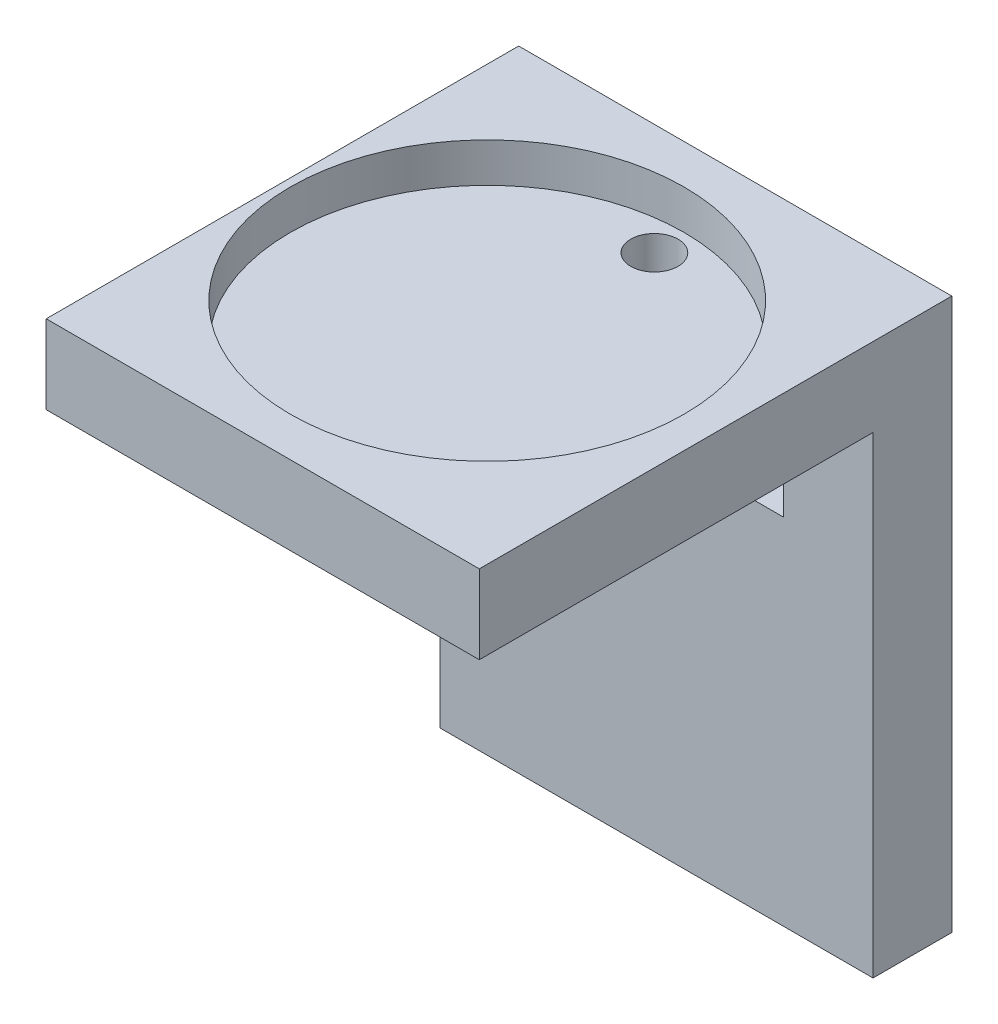
SolidWorks part; units mm, degrees
ref_plane "정면" through (0, 0, 0) normal (0, 0, 1) x (1, 0, 0)
ref_plane "윗면" through (0, 0, 0) normal (0, 1, 0) x (1, 0, 0)
ref_plane "우측면" through (0, 0, 0) normal (1, 0, 0) x (0, 0, -1)
sketch "Sketch1" plane through (0, 0, 0) normal (0, 1, 0) x (1, 0, 0)
  line L1 (0, 0) -> (670, 0)
  line L2 (0, 0) -> (0, 120)
  line L3 (0, 120) -> (670, 120)
  line L4 (670, 0) -> (670, 120)
  dimension "700" = 670
  dimension "D2" = 120
extrude "Boss-Extrude1" add sketch "Sketch1" along normal blind 530
sketch "Sketch2" plane through (0, 0, 0) normal (0, 0, 1) x (1, 0, 0)
  line L0 (0, 530) -> (0, 0) construction
  line L1 (10, 280) -> (110, 280)
  line L2 (10, 280) -> (10, 480)
  line L3 (10, 480) -> (110, 480)
  line L4 (110, 280) -> (110, 480)
  line L5 (0, 0) -> (670, 0) construction
  line L6 (120, 280) -> (120, 480)
  line L7 (120, 280) -> (220, 280)
  line L8 (220, 280) -> (220, 480)
  line L9 (120, 480) -> (220, 480)
  line L10 (230, 280) -> (230, 480)
  line L11 (230, 280) -> (330, 280)
  line L12 (330, 280) -> (330, 480)
  line L13 (230, 480) -> (330, 480)
  line L14 (340, 280) -> (340, 480)
  line L15 (340, 280) -> (440, 280)
  line L16 (440, 280) -> (440, 480)
  line L17 (340, 480) -> (440, 480)
  line L18 (450, 280) -> (450, 480)
  line L19 (450, 280) -> (550, 280)
  line L20 (550, 280) -> (550, 480)
  line L21 (450, 480) -> (550, 480)
  line L22 (560, 280) -> (560, 480)
  line L23 (560, 280) -> (660, 280)
  line L24 (660, 280) -> (660, 480)
  line L25 (560, 480) -> (660, 480)
  line L27 (10, 10) -> (660, 10)
  line L28 (10, 10) -> (10, 260)
  line L29 (10, 260) -> (660, 260)
  line L30 (660, 10) -> (660, 260)
  line L31 (0, 530) -> (670, 530) construction
  point P6 (10, 380)
  dimension "D1" = 100
  dimension "D2" = 200
  dimension "D3" = 10
  dimension "D4" = 50
  dimension "D6" = 10
  dimension "D7" = 20
  dimension "D5" = 6
extrude "Cut-Extrude1" cut sketch "Sketch2" against normal blind 100
sketch "Sketch3" plane through (0, 530, 0) normal (0, 1, 0) x (1, 0, 0)
  line L1 (670, 120) -> (0, 120) construction
  line L2 (0, 120) -> (0, 0) construction
  circle A0 centre (60, 60) radius 50
  circle A1 centre (170, 60) radius 50
  circle A2 centre (280, 60) radius 50
  circle A3 centre (390, 60) radius 50
  circle A4 centre (500, 60) radius 50
  circle A5 centre (610, 60) radius 50
  dimension "D1" = 100
  dimension "D2" = 10
  dimension "D3" = 10
  dimension "D4" = 6
extrude "Cut-Extrude2" cut sketch "Sketch3" against normal blind 260
hole_wizard "Ø12.0 (12) Diameter Hole2" positions "3DSketch1" profile "Sketch7" hole size "Ø12.0" standard "Ansi Metric"
sketch3d "3DSketch1"
  point P0 (59.7046, 270, -102.4117)
  point P2 (171.5567, 270, -102.6076)
  point P4 (280.8723, 270, -102.3969)
  point P6 (391.0687, 270, -102.7535)
  point P8 (500.7133, 270, -101.754)
  point P10 (609.5165, 270, -101.1227)
sketch "Sketch7" plane through (59.7046, 270, -102.4117) normal (1, 0, 0) x (0, 0, 1)
  line L0 (0, 0) -> (0, 33.6052)
  line L1 (0, 33.6052) -> (6, 30)
  line L2 (6, 30) -> (6, 0)
  line L5 (6, 0) -> (0, 0)
  line L10 (0, 33.6052) -> (-6, 30) construction
  line L11 (0, -6.35) -> (0, 107.95) construction
  dimension "구멍 지름" = 12
  dimension "구멍 깊이" = 30
  dimension "드릴 각도" = 118
sketch "Sketch8" plane through (0, 0, 0) normal (0, 0, 1) x (1, 0, 0)
  line L0 (660, 280) -> (660, 480) construction
  line L1 (10, 280) -> (660, 280)
  line L2 (10, 280) -> (10, 330)
  line L3 (10, 330) -> (660, 330)
  line L4 (660, 280) -> (660, 330)
  dimension "D1" = 50
extrude "Boss-Extrude2" add sketch "Sketch8" against normal blind 5
sketch "Sketch9" plane through (670, 0, 0) normal (1, 0, 0) x (0, 0, -1)
  line L0 (0, 530) -> (0, 0) construction
  line L1 (10, 10) -> (20, 10)
  line L2 (10, 10) -> (10, 260)
  line L3 (10, 260) -> (20, 260)
  line L4 (20, 10) -> (20, 260)
  line L5 (0, 0) -> (120, 0) construction
  dimension "D1" = 10
  dimension "D2" = 10
  dimension "D3" = 10
  dimension "D4" = 250
extrude "Cut-Extrude3" cut sketch "Sketch9" against normal blind 717
sketch "Sketch10" plane through (0, 10, 0) normal (0, 1, 0) x (1, 0, 0)
  line L0 (670, 120) -> (0, 120) construction
  line L1 (365, 61.9436) -> (350, 87.9243)
  line L2 (350, 87.9243) -> (320, 87.9243)
  line L3 (320, 87.9243) -> (305, 61.9436)
  line L4 (305, 61.9436) -> (320, 35.9628)
  line L5 (320, 35.9628) -> (350, 35.9628)
  line L6 (350, 35.9628) -> (365, 61.9436)
  line L7 (0, 120) -> (0, 0) construction
  circle A0 centre (335, 61.9436) radius 25.9808 construction
  dimension "D1" = 60
  dimension "D2" = 305
extrude "Cut-Extrude4" cut sketch "Sketch10" against normal blind 5
sketch "Sketch11" plane through (0, 0, -100) normal (0, 0, 1) x (1, 0, 0)
  line L0 (10, 10) -> (660, 10) construction
  line L1 (250, 10) -> (260, 10)
  line L2 (250, 10) -> (250, 110)
  line L3 (250, 110) -> (260, 110)
  line L4 (260, 10) -> (260, 110)
  line L5 (660, 10) -> (660, 260) construction
  line L6 (410, 10) -> (420, 10)
  line L7 (410, 10) -> (410, 110)
  line L8 (410, 110) -> (420, 110)
  line L9 (420, 10) -> (420, 110)
  line L10 (25, 198.4569) -> (325, 145.5588)
  line L11 (325, 145.5588) -> (325, 122.0178)
  line L12 (325, 122.0178) -> (345, 122.0178)
  line L13 (345, 122.0178) -> (345, 145.5588)
  line L14 (345, 145.5588) -> (645, 198.4569)
  line L15 (645, 198.4569) -> (25, 198.4569)
  point P18 (345, 133.7883)
  dimension "D1" = 10
  dimension "D2" = 10
  dimension "D3" = 100
  dimension "D4" = 100
  dimension "D5" = 150
  dimension "D6" = 240
  dimension "D7" = 20
  dimension "D8" = 65
  dimension "D9" = 100
  dimension "D10" = 620
  dimension "D11" = 100
extrude "Boss-Extrude3" add sketch "Sketch11" along normal blind 78 separate body
sketch "Sketch12" plane through (0, 0, -100) normal (0, 0, 1) x (1, 0, 0)
  line L0 (660, 260) -> (10, 260) construction
  line L1 (75.1986, 260) -> (95.1986, 260)
  line L2 (75.1986, 260) -> (75.1986, 230)
  line L3 (75.1986, 230) -> (95.1986, 230)
  line L4 (95.1986, 260) -> (95.1986, 230)
  line L5 (65.1986, 260) -> (65.1986, 240) construction
  line L6 (185.1986, 260) -> (185.1986, 230)
  line L7 (185.1986, 260) -> (205.1986, 260)
  line L8 (205.1986, 260) -> (205.1986, 230)
  line L9 (185.1986, 230) -> (205.1986, 230)
  line L10 (295.1986, 260) -> (295.1986, 230)
  line L11 (295.1986, 260) -> (315.1986, 260)
  line L12 (315.1986, 260) -> (315.1986, 230)
  line L13 (295.1986, 230) -> (315.1986, 230)
  line L14 (405.1986, 260) -> (405.1986, 230)
  line L15 (405.1986, 260) -> (425.1986, 260)
  line L16 (425.1986, 260) -> (425.1986, 230)
  line L17 (405.1986, 230) -> (425.1986, 230)
  line L18 (515.1986, 260) -> (515.1986, 230)
  line L19 (515.1986, 260) -> (535.1986, 260)
  line L20 (535.1986, 260) -> (535.1986, 230)
  line L21 (515.1986, 230) -> (535.1986, 230)
  line L22 (625.1986, 260) -> (625.1986, 230)
  line L23 (625.1986, 260) -> (645.1986, 260)
  line L24 (645.1986, 260) -> (645.1986, 230)
  line L25 (625.1986, 230) -> (645.1986, 230)
  dimension "D1" = 20
  dimension "D2" = 30
  dimension "D3" = 10
  dimension "D4" = 6
extrude "Cut-Extrude5" cut sketch "Sketch12" against normal blind 80
sketch "Sketch15" plane through (345, 0, 0) normal (1, 0, 0) x (0, 0, -1)
  line L0 (20, 10) -> (20, 260) construction
  line L1 (20, 121.4638) -> (50, 121.4638)
  line L2 (20, 121.4638) -> (20, 145)
  line L3 (20, 145) -> (50, 145)
  line L4 (50, 121.4638) -> (50, 145)
  line L5 (120, 530) -> (120, 0) construction
  line L6 (100, 116.0134) -> (70, 116.0134)
  line L7 (100, 116.0134) -> (100, 145)
  line L8 (100, 145) -> (70, 145)
  line L9 (70, 116.0134) -> (70, 145)
  line L10 (20, 260) -> (10, 260) construction
  dimension "D1" = 20
  dimension "D2" = 20
  dimension "D3" = 115
  dimension "D4" = 30
extrude "Cut-Extrude7" cut sketch "Sketch15" against normal blind 35
shell "Shell1" thickness 3
sketch "Sketch16" plane through (0, 122.0178, 0) normal (0, -1, 0) x (1, 0, 0)
  line L0 (345, -50) -> (325, -50) construction
  line L1 (328, -53) -> (342, -53)
  line L2 (328, -53) -> (328, -67)
  line L3 (328, -67) -> (342, -67)
  line L4 (342, -53) -> (342, -67)
  line L5 (325, -50) -> (325, -70) construction
  line L6 (345, -50) -> (345, -70) construction
  line L7 (325, -70) -> (345, -70) construction
  dimension "D1" = 3
  dimension "D2" = 3
  dimension "D3" = 3
  dimension "D4" = 3
extrude "Cut-Extrude8" cut sketch "Sketch16" against normal blind 35
sketch "Sketch17" plane through (0, 0, 0) normal (0, 0, 1) x (1, 0, 0)
  text T0 "<b>DIFF_USER</b>" font "Britannic Bold" height in points 72
extrude "Boss-Extrude4" add sketch "Sketch17" along normal blind 5
sketch "Sketch18" plane through (0, 0, 0) normal (0, 0, 1) x (1, 0, 0)
  line L0 (0, 530) -> (670, 530) construction
  line L1 (0, 530) -> (670, 530)
  line L2 (0, 530) -> (0, 280)
  line L3 (0, 280) -> (670, 280)
  line L4 (670, 530) -> (670, 280)
  line L5 (670, 530) -> (670, 0) construction
  line L6 (0, 0) -> (670, 0) construction
  dimension "D1" = 280
extrude "Cut-Extrude10" cut sketch "Sketch18" against normal through all both and the other way through all
delete or keep bodies "Body-Delete/Keep 2" type delete bodies bodies 109 115 112
sketch "Sketch19" plane through (0, 0, -120) normal (0, 0, -1) x (-1, 0, 0)
  line L0 (0, 280) -> (-670, 280) construction
  line L1 (0, 0) -> (-448, 0)
  line L2 (0, 0) -> (0, 280)
  line L3 (0, 280) -> (-448, 280)
  line L4 (-448, 0) -> (-448, 280)
  line L6 (-670, 0) -> (-558, 0)
  line L7 (-670, 0) -> (-670, 280)
  line L8 (-670, 280) -> (-558, 280)
  line L9 (-558, 0) -> (-558, 280)
  dimension "D1" = 110
  dimension "D2" = 448
extrude "Cut-Extrude11" cut sketch "Sketch19" against normal through all both and the other way through all
sketch "Sketch20" plane through (0, 0, -100) normal (0, 0, 1) x (1, 0, 0)
  line L0 (558, 10) -> (558, 260) construction
  line L1 (448, 0) -> (558, 0)
  line L2 (448, 0) -> (448, 140)
  line L3 (448, 140) -> (558, 140)
  line L4 (558, 0) -> (558, 140)
  dimension "D1" = 140
extrude "Cut-Extrude12" cut sketch "Sketch20" against normal through all both and the other way through all
